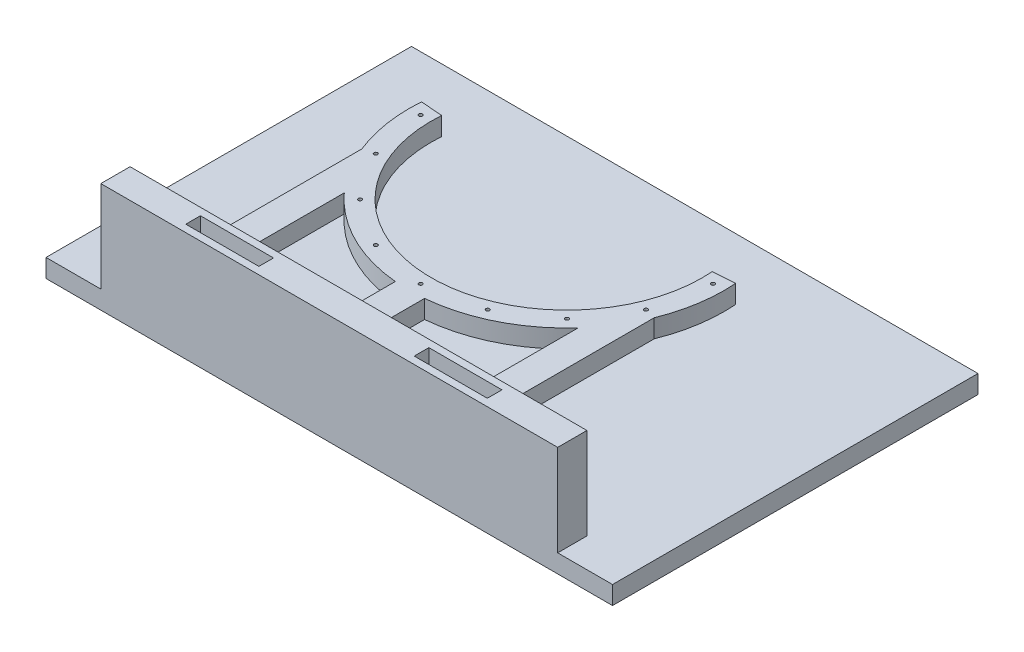
SolidWorks part; units mm, degrees
ref_plane "前视基准面" through (0, 0, 0) normal (0, 0, 1) x (1, 0, 0)
ref_plane "上视基准面" through (0, 0, 0) normal (0, 1, 0) x (1, 0, 0)
ref_plane "右视基准面" through (0, 0, 0) normal (1, 0, 0) x (0, 0, -1)
sketch "草图1" plane through (0, 0, 0) normal (0, 1, 0) x (1, 0, 0)
  line L1 (0, 0) -> (155, 0)
  line L2 (0, 0) -> (0, 100)
  line L3 (0, 100) -> (155, 100)
  line L4 (155, 0) -> (155, 100)
  dimension "D1" = 155
  dimension "D2" = 100
extrude "凸台-拉伸1" add sketch "草图1" along normal blind 5
sketch "草图2" plane through (0, 5, 0) normal (0, 1, 0) x (1, 0, 0)
  line L0 (0, 0) -> (155, 0) construction
  line L1 (15, 0) -> (140, 0)
  line L2 (15, 0) -> (15, 8)
  line L3 (15, 8) -> (140, 8)
  line L4 (140, 0) -> (140, 8)
  line L5 (0, 100) -> (0, 0) construction
  line L6 (155, 0) -> (155, 100) construction
  dimension "D1" = 15
  dimension "D2" = 15
  dimension "D3" = 8
extrude "凸台-拉伸2" add sketch "草图2" along normal blind 25
sketch "草图3" plane through (0, 0, -8) normal (0, 0, -1) x (-1, 0, 0)
  line L0 (-77.5, 30) -> (-77.5, 5) construction
  line L1 (-140, 5) -> (-15, 5) construction
  line L3 (-62, 30) -> (-62, 5) construction
  line L4 (-50.5, 30) -> (-50.5, 5) construction
  line L5 (-39.5, 30) -> (-39.5, 5) construction
  line L6 (-37.5, 30) -> (-37.5, 5) construction
  point P4 (-77.5, 5)
  point P5 (-50.5, 5)
  point P13 (-62, 5)
  point P15 (-50.5, 5)
  point P16 (-39.5, 5)
  point P17 (-37.5, 5)
  dimension "D1" = 15.5
  dimension "D2" = 27
  dimension "D3" = 38
  dimension "D4" = 40
sketch3d "3D草图2"
  line L0 (77.5, 30, -8) -> (77.5, 5, -8) construction
  line L1 (62, 30, -8) -> (62, 5, -8) construction
  line L2 (50.5, 30, -8) -> (50.5, 5, -8) construction
  line L3 (39.5, 30, -8) -> (39.5, 5, -8) construction
  line L4 (37.5, 30, -8) -> (37.5, 5, -8) construction
sketch "草图4" plane through (0, 0, -8) normal (0, 0, -1) x (-1, 0, 0)
  line L0 (-140, 25) -> (-15, 25) construction
  line L3 (-140, 5) -> (-15, 5) construction
  dimension "D1" = 20
sketch3d "3D草图3" plane through (0, 0, 0) normal (0, 0, 1) x (1, 0, 0)
sketch "草图5" plane through (0, 5, 0) normal (0, 1, 0) x (1, 0, 0)
  line L0 (77.5, 100) -> (77.5, 0) construction
  line L1 (155, 100) -> (0, 100) construction
  line L2 (15, 0) -> (140, 0) construction
sketch "草图6" plane through (0, 5, 0) normal (0, 1, 0) x (1, 0, 0)
  line L0 (37.5, 8) -> (37.5, 50008) construction
  line L1 (140, 8) -> (15, 8) construction
  line L2 (39.5, 8) -> (39.5, 50008) construction
  line L3 (50.5, 8) -> (50.5, 50008) construction
  line L4 (62, 8) -> (62, 50008) construction
  line L5 (77.5, -3.6088) -> (77.5, 49996.3912) construction
  line L6 (-962.5, 65) -> (49037.5, 65) construction
  point P16 (77.5, 25)
  point P17 (37.5, 65)
  point P18 (117.5, 65)
  dimension "D1" = 40
  dimension "D2" = 40
  dimension "D3" = 40
  dimension "D4" = 17
sketch "草图7" plane through (0, 5, 0) normal (0, 1, 0) x (1, 0, 0)
  line L0 (37.5, -199992) -> (37.5, 250008) construction
  line L1 (34.5084, 68.2244) -> (40.4916, 67.7756)
  line L2 (114.5084, 67.7756) -> (120.4916, 68.2244)
  arc A0 (37.5, 65) -> (117.5, 65) centre (77.5, 65) ccw construction
  arc A3 (37.5, 68) -> (117.5, 68) centre (77.5, 65) ccw construction
  arc A4 (34.5084, 68.2244) -> (120.4916, 68.2244) centre (77.5, 65) ccw
  arc A5 (40.4916, 67.7756) -> (114.5084, 67.7756) centre (77.5, 65) ccw
  dimension "D1" = 3
  dimension "D3" = 3
  dimension "D2" = 3
  dimension "D4" = 3
extrude "凸台-拉伸6" add sketch "草图7" along normal blind 20
sketch "草图11" plane through (0, 0, -8) normal (0, 0, -1) x (-1, 0, 0)
  line L0 (-81.5, 25) -> (-73.5, 25)
  line L1 (-81.5, 25) -> (-81.5, 20)
  line L2 (-73.5, 25) -> (-73.5, 20)
  line L3 (-81.5, 20) -> (-73.5, 20)
  line L4 (-140, 25) -> (-15, 25) construction
  line L5 (-77.5, 200030) -> (-77.5, -199995) construction
  line L6 (-37.5, 200030) -> (-37.5, -199995) construction
  line L7 (-37.5, 25) -> (-45.5, 25)
  line L8 (-37.5, 25) -> (-37.5, 20)
  line L9 (-37.5, 20) -> (-45.5, 20)
  line L10 (-45.5, 25) -> (-45.5, 20)
  line L12 (-117.5, 25) -> (-109.5, 25)
  line L13 (-117.5, 25) -> (-117.5, 20)
  line L14 (-117.5, 20) -> (-109.5, 20)
  line L15 (-109.5, 25) -> (-109.5, 20)
  dimension "D1" = 4
  dimension "D2" = 4
  dimension "D3" = 5
  dimension "D4" = 8
  dimension "D5" = 8
  dimension "D6" = 28
  dimension "D7" = 28
extrude "凸台-拉伸7" add sketch "草图11" along normal up to next
sketch "草图12" plane through (0, 0, -8) normal (0, 0, -1) x (-1, 0, 0)
  line L0 (-140, 30) -> (-140, 5) construction
  line L1 (-140, 20) -> (-15, 20)
  line L2 (-140, 20) -> (-140, 5)
  line L3 (-140, 5) -> (-15, 5)
  line L4 (-15, 20) -> (-15, 5)
  line L5 (-15, 30) -> (-15, 5) construction
  line L6 (-140, 30) -> (-15, 30) construction
  dimension "D1" = 10
  dimension "D2" = 15
extrude "切除-拉伸1" cut sketch "草图12" along normal blind 130 contours L1 L4 L3 L2
sketch3d "3D草图4" plane through (0, 0, 0) normal (0, 0, 1) x (1, 0, 0)
  dimension "D1" = 2
sketch "草图16" plane through (0, 18, 0) normal (0, -1, 0) x (-1, 0, 0)
  line L0 (-74.5, 25) -> (-80.5, 25) construction
  line L1 (-80.5, 25) -> (-74.5, 25)
  arc A2 (-74.5, 25) -> (-80.5, 25) centre (-77.5, 25) cw
revolve "切除-旋转3" cut sketch "草图16" angle 360 about L0
pattern_circular "阵列(圆周)1" count 5 every 22.5 about axis through (77.5, 0, -65) along (0, 1, 0) of "切除-旋转3"
sketch "草图17" plane through (0, 25, 0) normal (0, 1, 0) x (1, 0, 0)
  line L0 (37.5, 63.7194) -> (37.5, 67.5612) construction
  line L1 (37.5, -199992) -> (37.5, 250008) construction
  circle A0 centre (37.5, 64.9948) radius 0.5
  point P4 (37.5, 64.9948)
  point P7 (0, 0)
  dimension "D1" = 1
extrude "切除-拉伸2" cut sketch "草图17" against normal up to next
pattern_circular "阵列(圆周)2" count 9 over 180 about axis through (77.5, 0, -65) along (0, 1, 0) of "切除-拉伸2"
sketch "草图19" plane through (0, 30, 0) normal (0, 1, 0) x (1, 0, 0)
  line L0 (77.5, 0) -> (77.5, 8) construction
  line L1 (15, 0) -> (140, 0) construction
  line L2 (140, 8) -> (15, 8) construction
  line L3 (15, 4) -> (140, 4) construction
  line L4 (15, 8) -> (15, 0) construction
  line L5 (140, 0) -> (140, 8) construction
  line L6 (77.5, 0) -> (15, 8) construction
  line L7 (77.5, 8) -> (15, 0) construction
  line L8 (140, 8) -> (77.5, 0) construction
  line L9 (77.5, 8) -> (140, 0) construction
  line L11 (36.25, 6) -> (56.25, 6)
  line L12 (36.25, 6) -> (36.25, 2)
  line L13 (36.25, 2) -> (56.25, 2)
  line L14 (56.25, 6) -> (56.25, 2)
  line L15 (36.25, 6) -> (56.25, 2) construction
  line L16 (36.25, 2) -> (56.25, 6) construction
  line L17 (98.75, 2) -> (118.75, 2)
  line L18 (98.75, 2) -> (98.75, 6)
  line L19 (98.75, 6) -> (118.75, 6)
  line L20 (118.75, 2) -> (118.75, 6)
  line L21 (98.75, 2) -> (118.75, 6) construction
  line L22 (98.75, 6) -> (118.75, 2) construction
  point P17 (46.25, 4)
  point P25 (108.75, 4)
extrude "切除-拉伸3" cut sketch "草图19" against normal blind 15
